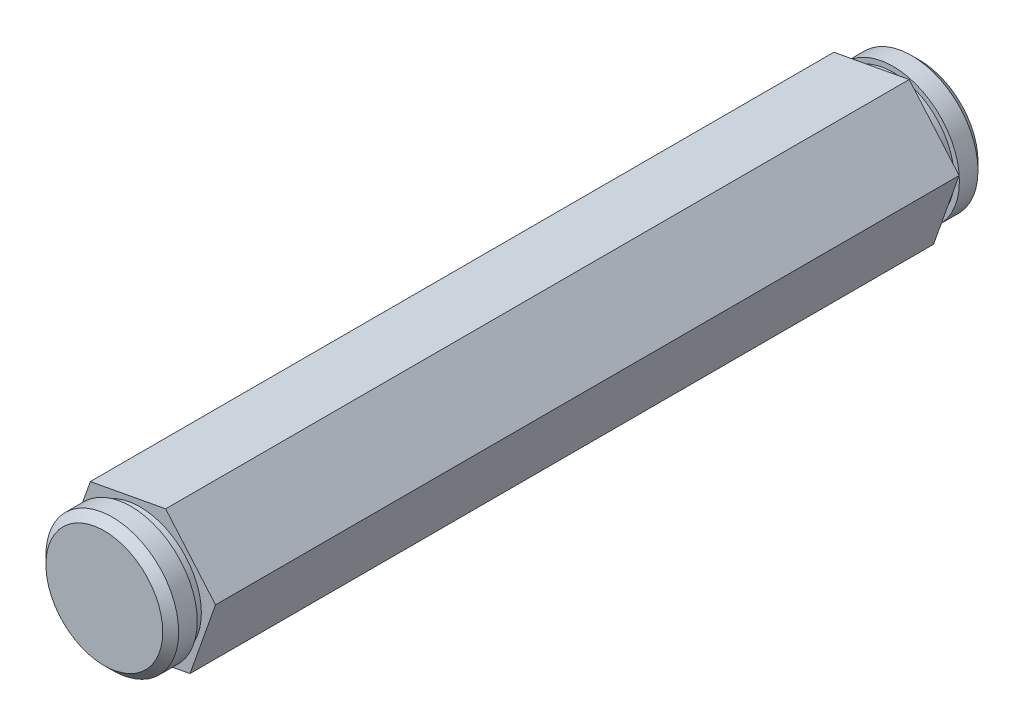
SolidWorks part; units mm, degrees
ref_plane "Front Plane" through (0, 0, 0) normal (0, 0, 1) x (1, 0, 0)
ref_plane "Top Plane" through (0, 0, 0) normal (0, 1, 0) x (1, 0, 0)
ref_plane "Right Plane" through (0, 0, 0) normal (1, 0, 0) x (0, 0, -1)
sketch "Sketch1" plane through (0, 0, 0) normal (0, 0, 1) x (1, 0, 0)
  line L1 (-2.4404, -6.9143) -> (4.7678, -5.5706)
  line L2 (4.7678, -5.5706) -> (7.2082, 1.3438)
  line L3 (7.2082, 1.3438) -> (2.4404, 6.9143)
  line L4 (2.4404, 6.9143) -> (-4.7678, 5.5706)
  line L5 (-4.7678, 5.5706) -> (-7.2082, -1.3438)
  line L6 (-7.2082, -1.3438) -> (-2.4404, -6.9143)
  circle A0 centre (0, 0) radius 6.35 construction
  dimension "D1" = 12.7
extrude "Boss-Extrude1" add sketch "Sketch1" along normal mid plane 71.12
sketch "Sketch2" plane through (0, 0, 35.56) normal (0, 0, 1) x (1, 0, 0)
  circle A0 centre (0, 0) radius 5.8547
  dimension "D1" = 11.7094
extrude "Boss-Extrude2" add sketch "Sketch2" along normal blind 0.889
sketch "Sketch3" plane through (0, 0, 36.449) normal (0, 0, 1) x (1, 0, 0)
  circle A0 centre (0, 0) radius 6.35
  dimension "D1" = 12.7
extrude "Boss-Extrude3" add sketch "Sketch3" along normal blind 2.54
chamfer "Chamfer1" distance 0.762 angle 45 1 edges at (6.35, 0, 38.989)
mirror "Mirror1" about plane through (0, 0, 0) normal (0, 0, 1) of "Boss-Extrude2", "Boss-Extrude3", "Chamfer1"
